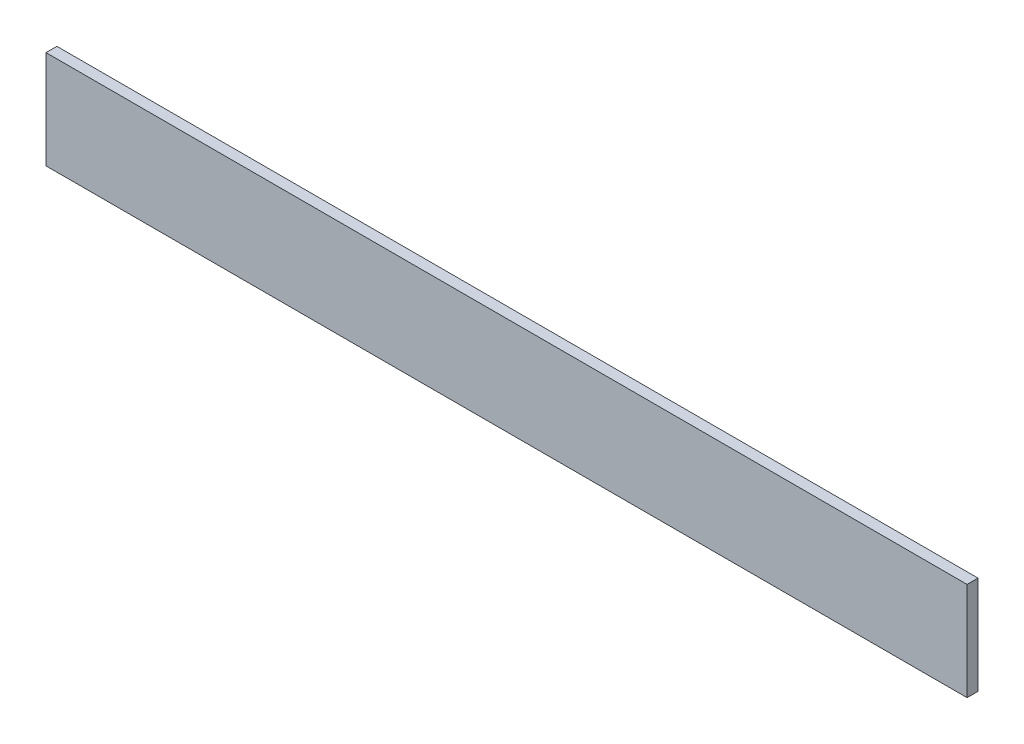
SolidWorks part; units mm, degrees
ref_plane "Front Plane" through (0, 0, 0) normal (0, 0, 1) x (1, 0, 0)
ref_plane "Top Plane" through (0, 0, 0) normal (0, 1, 0) x (1, 0, 0)
ref_plane "Right Plane" through (0, 0, 0) normal (1, 0, 0) x (0, 0, -1)
sketch "Sketch1" plane through (0, 0, 0) normal (0, 0, 1) x (1, 0, 0)
  line L1 (-84.5, 9) -> (84.5, 9)
  line L2 (-84.5, 9) -> (-84.5, -9)
  line L3 (-84.5, -9) -> (84.5, -9)
  line L4 (84.5, 9) -> (84.5, -9)
  line L5 (-84.5, 9) -> (84.5, -9) construction
  line L6 (-84.5, -9) -> (84.5, 9) construction
  point P0 (0, 0)
  dimension "D1" = 18
  dimension "D2" = 169
extrude "Boss-Extrude1" add sketch "Sketch1" along normal blind 2
